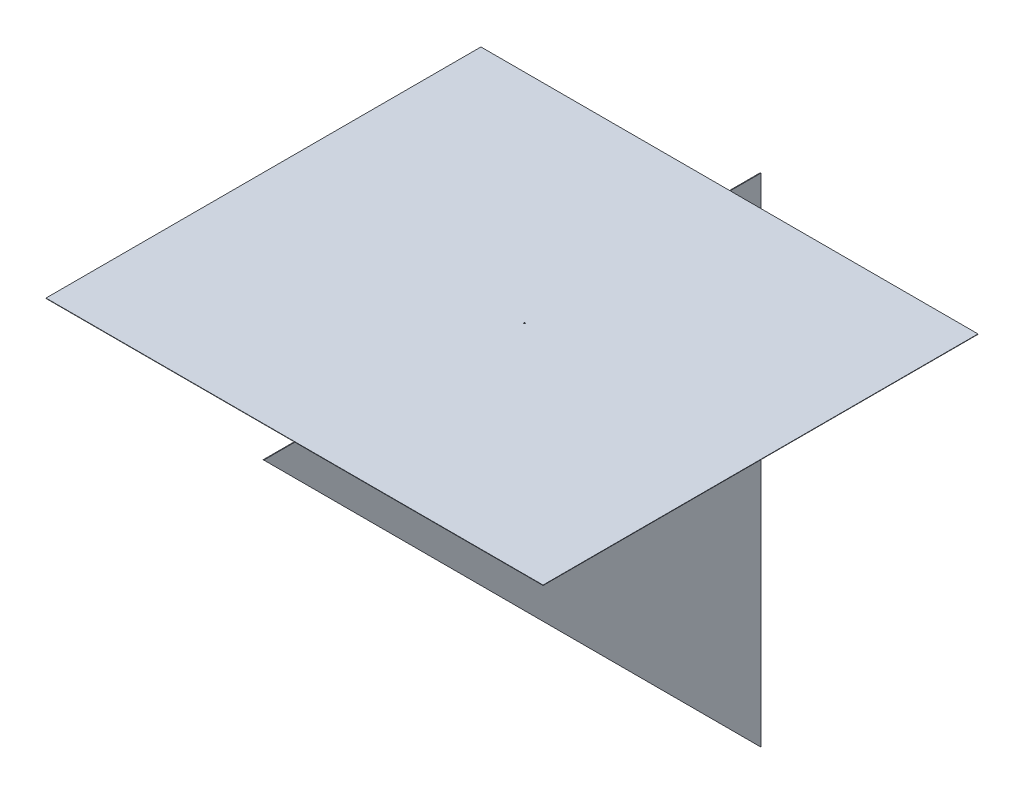
SolidWorks part; units mm, degrees
material "Кованая нержавеющая сталь"
ref_plane "Front" through (0, 0, 0) normal (0, 0, 1) x (1, 0, 0)
ref_plane "Top" through (0, 0, 0) normal (0, 1, 0) x (1, 0, 0)
ref_plane "Right" through (0, 0, 0) normal (1, 0, 0) x (0, 0, -1)
sketch "Эскиз1" plane through (0, 0, 0) normal (1, 0, 0) x (0, 0, -1)
  line L0 (-4000, 4000) -> (0, 0)
  line L2 (0, 0) -> (0, 4000)
  line L3 (0, 4000) -> (-4000, 4000)
  dimension "D1" = 4000
  dimension "D2" = 4000
extrude "Бобышка-Вытянуть1" add sketch "Эскиз1" along normal blind 5
sketch "Эскиз2" plane through (0, 4000, 0) normal (0, 1, 0) x (1, 0, 0)
  line L0 (0, 0) -> (5, -4000) construction
  line L1 (102.5, -2000) -> (-97.5, -2000) construction
  line L4 (-1997.5, -3750) -> (2002.5, -3750)
  line L5 (-1997.5, -3750) -> (-1997.5, -250)
  line L6 (-1997.5, -250) -> (2002.5, -250)
  line L7 (2002.5, -3750) -> (2002.5, -250)
  line L8 (-1997.5, -3750) -> (2002.5, -250) construction
  line L9 (-1997.5, -250) -> (2002.5, -3750) construction
  circle A0 centre (-97.5, -2000) radius 0.5
  circle A1 centre (102.5, -2000) radius 5
  point P7 (2.5, -2000)
  point P9 (2.5, -2000)
  dimension "D4" = 1
  dimension "D5" = 10
  dimension "D1" = 3500
  dimension "D2" = 4000
  dimension "D3" = 200
extrude "Бобышка-Вытянуть2" add sketch "Эскиз2" along normal blind 3
